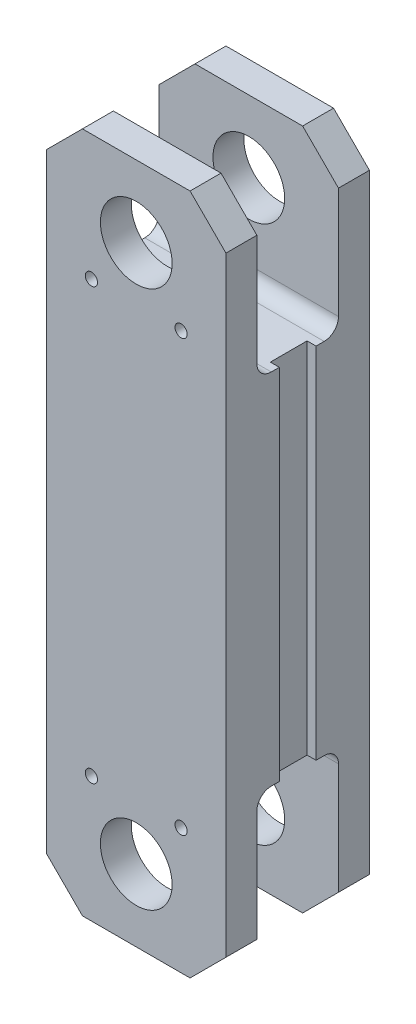
SolidWorks part; units mm, degrees
ref_plane "前视基准面" through (0, 0, 0) normal (0, 0, 1) x (1, 0, 0)
ref_plane "上视基准面" through (0, 0, 0) normal (0, 1, 0) x (1, 0, 0)
ref_plane "右视基准面" through (0, 0, 0) normal (1, 0, 0) x (0, 0, -1)
sketch "草图1" plane through (0, 0, 0) normal (0, 0, 1) x (1, 0, 0)
  line L1 (50, -190) -> (-50, -190)
  line L2 (50, -190) -> (50, 190)
  line L3 (50, 190) -> (-50, 190)
  line L4 (-50, -190) -> (-50, 190)
  line L5 (50, -190) -> (-50, 190) construction
  line L6 (50, 190) -> (-50, -190) construction
  point P0 (0, 0)
  dimension "D1" = 380
  dimension "D2" = 100
extrude "凸台-拉伸1" add sketch "草图1" along normal blind 80
sketch "草图2" plane through (50, 0, 0) normal (1, 0, 0) x (0, 0, -1)
  line L0 (-40, 190) -> (-40, -190) construction
  line L1 (-80, 190) -> (0, 190) construction
  line L2 (-80, -190) -> (0, -190) construction
  line L3 (-62.75, 190) -> (-62.75, 100)
  line L4 (-62.75, 100) -> (-17.25, 100)
  line L5 (-17.25, 100) -> (-17.25, 190)
  line L6 (-17.25, 190) -> (-62.75, 190)
  dimension "D1" = 45.5
  dimension "D2" = 90
extrude "切除-拉伸1" cut sketch "草图2" against normal up to next
sketch "草图3" plane through (50, 0, 0) normal (1, 0, 0) x (0, 0, -1)
  line L0 (-40, 100) -> (-40, -190) construction
  line L1 (-62.75, 100) -> (-17.25, 100) construction
  line L2 (-80, -190) -> (0, -190) construction
  line L3 (-50.25, 100) -> (-50.25, -190)
  line L4 (-50.25, -190) -> (-29.75, -190)
  line L5 (-29.75, -190) -> (-29.75, 100)
  line L6 (-29.75, 100) -> (-50.25, 100)
  dimension "D1" = 20.5
extrude "切除-拉伸2" cut sketch "草图3" against normal blind 5
mirror "镜向1" about plane through (0, 0, 0) normal (0, 1, 0) of "切除-拉伸1"
mirror "镜向2" about plane through (0, 0, 0) normal (1, 0, 0) of "切除-拉伸2"
sketch "草图4" plane through (0, 0, 80) normal (0, 0, 1) x (1, 0, 0)
  line L0 (0, 190) -> (0, -190) construction
  line L1 (50, 190) -> (-50, 190) construction
  line L2 (-50, -190) -> (50, -190) construction
  line L3 (0, 0) -> (108.9197, 0) construction
  circle A0 centre (0, 150) radius 20
  dimension "D1" = 40
  dimension "D2" = 300
extrude "切除-拉伸3" cut sketch "草图4" against normal through all
mirror "镜向3" about plane through (0, 0, 0) normal (0, 1, 0) of "切除-拉伸3"
hole_wizard "M8 螺纹孔1" positions "草图6" profile "草图7" tap size "M8" standard "GB"
sketch "草图6" plane through (0, 0, 80) normal (0, 0, 1) x (1, 0, 0)
  line L0 (0, 0) -> (0, 119.3051) construction
  circle A0 centre (0, 150) radius 20 construction
  point P0 (-25, 120)
  point P3 (25, 120)
  point P10 (0, 0)
  dimension "D2" = 30
  dimension "D1" = 50
sketch "草图7" plane through (-25, 120, 80) normal (1, 0, 0) x (0, -1, 0)
  line L0 (0, 0) -> (0, 80)
  line L1 (0, 80) -> (3.4, 80)
  line L2 (3.4, 80) -> (3.4, 0)
  line L5 (3.4, 0) -> (0, 0)
  line L11 (0, -6.35) -> (0, 107.95) construction
  dimension "通孔螺纹孔钻头直径" = 6.8
  dimension "通孔螺纹孔钻头深度" = 80
cosmetic thread "孔螺蚊线1" parameters "D2"=8
cosmetic thread "孔螺蚊线2" parameters "D2"=8
mirror "镜向4" about plane through (0, 0, 0) normal (0, 1, 0) of "M8 螺纹孔1"
fillet "圆角1" radius 8 4 edges at (0, -100, 17.25) (0, -100, 62.75) (0, 100, 62.75) (0, 100, 17.25)
chamfer "倒角1" distance 20 angle 45 8 edges at (-50, 190, 8.625) (50, 190, 8.625) (50, 190, 71.375) (-50, 190, 71.375) (-50, -190, 71.375) (50, -190, 71.375) (-50, -190, 8.625) (50, -190, 8.625)
